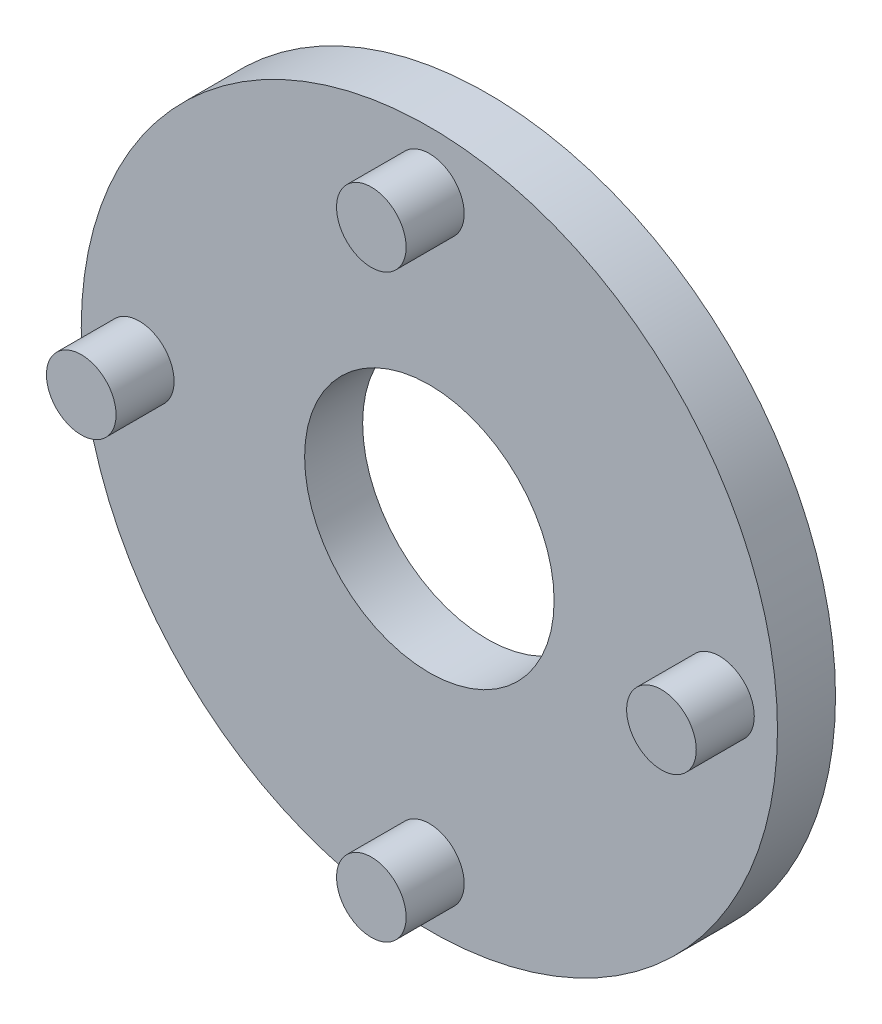
SolidWorks part; units mm, degrees
ref_plane "前视基准面" through (0, 0, 0) normal (0, 0, 1) x (1, 0, 0)
ref_plane "上视基准面" through (0, 0, 0) normal (0, 1, 0) x (1, 0, 0)
ref_plane "右视基准面" through (0, 0, 0) normal (1, 0, 0) x (0, 0, -1)
sketch "草图1" plane through (0, 0, 0) normal (0, 0, 1) x (1, 0, 0)
  line L0 (0, -33.1708) -> (0, -5.9499) construction
  line L1 (0.0627, 0) -> (13.4223, 0) construction
  circle A0 centre (25, 0) radius 3
  circle A1 centre (0, -25) radius 3
  circle A2 centre (-25, 0) radius 3
  circle A3 centre (0, 25) radius 3
  point P3 (0, 0)
  point P4 (0, 27.2209)
  point P11 (0, 0)
  point P12 (0, 0)
  dimension "D3" = 6
  dimension "D2" = 25
  dimension "D1" = 4
extrude "凸台-拉伸1" add sketch "草图1" against normal up to surface (5 mm away)
sketch "草图2" plane through (0, 0, -5) normal (0, 0, -1) x (-1, 0, 0)
  circle A0 centre (0, 0) radius 30
  dimension "D1" = 60
extrude "凸台-拉伸2" add sketch "草图2" along normal up to surface (5 mm away)
sketch "草图3" plane through (0, 0, -10) normal (0, 0, -1) x (-1, 0, 0)
  circle A0 centre (0, 0) radius 10.75
  circle A1 centre (0, 0) radius 30
  circle A2 centre (0, 0) radius 30
  dimension "D2" = 21.5
  dimension "D1" = 0
extrude "切除-拉伸1" cut sketch "草图3" against normal up to surface (5 mm away) contours A0 up to face at (-3, 25, -5)
sketch "草图4" plane through (0, 0, -10) normal (0, 0, -1) x (-1, 0, 0)
  circle A0 centre (0, 0) radius 15
  circle A1 centre (0, 0) radius 17
  dimension "D1" = 30
  dimension "D2" = 34
extrude "切除-拉伸3" cut sketch "草图4" against normal blind 3
